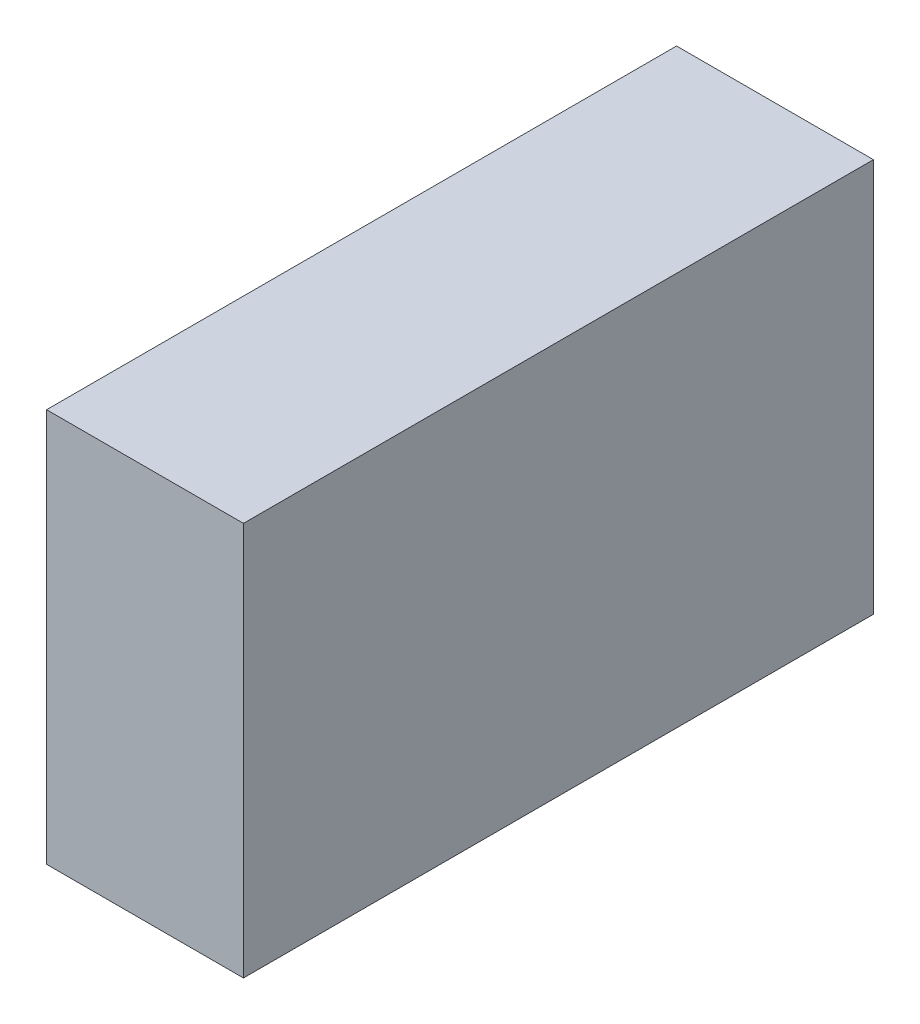
SolidWorks part; units mm, degrees
ref_plane "front" through (0, 0, 0) normal (0, 0, 1) x (1, 0, 0)
ref_plane "top" through (0, 0, 0) normal (0, 1, 0) x (1, 0, 0)
ref_plane "right" through (0, 0, 0) normal (1, 0, 0) x (0, 0, -1)
sketch "Sketch1" plane through (0, 0, 0) normal (0, 0, 1) x (1, 0, 0)
  line L1 (-15.875, 63.5) -> (15.875, 63.5)
  line L2 (-15.875, 63.5) -> (-15.875, 0)
  line L3 (-15.875, 0) -> (15.875, 0)
  line L4 (15.875, 63.5) -> (15.875, 0)
  dimension "D1" = 31.75
  dimension "D2" = 63.5
extrude "Extrude1" add sketch "Sketch1" against normal blind 101.6
